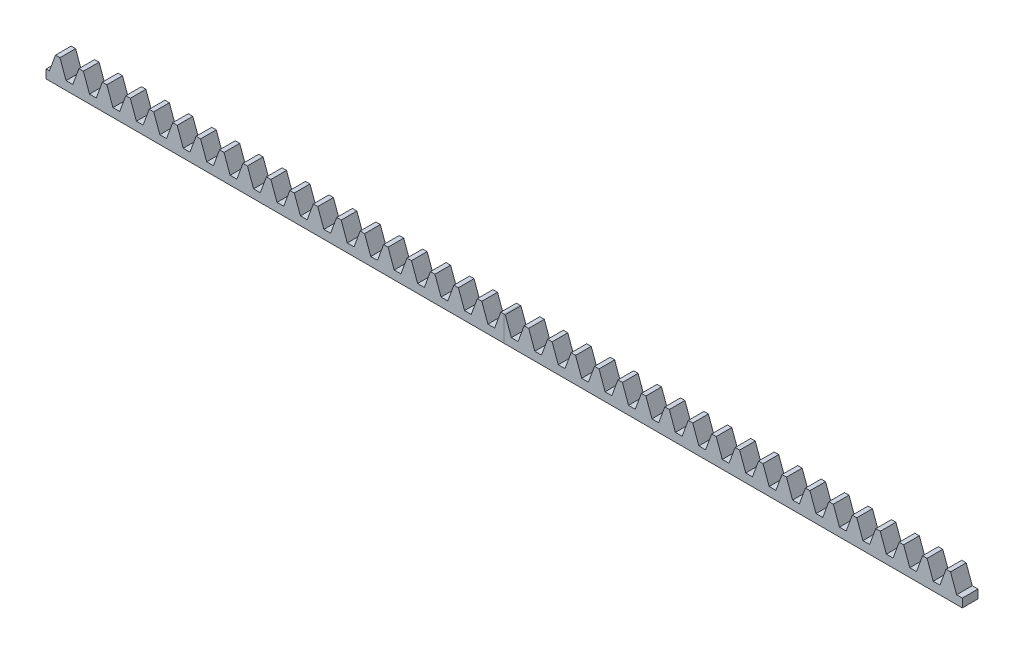
SolidWorks part; units mm, degrees
extrude "Blank" add sketch "BlankSke" against normal blind 8.89
sketch "BlankSke" plane through (0, 0, 0) normal (0, 0, 1) x (1, 0, 0)
  line L1 (0, 0) -> (519.999, 0)
  line L2 (0, 0) -> (0, 14.3933)
  line L3 (0, 14.3933) -> (519.999, 14.3933)
  line L4 (519.999, 0) -> (519.999, 14.3933)
  dimension "Length" = 519.999
  dimension "Blank_height" = 14.3933
ref_plane "Plane1" through (0, 0, 0) normal (0, 0, 1) x (1, 0, 0)
ref_plane "Plane2" through (0, 0, 0) normal (0, 1, 0) x (1, 0, 0)
ref_plane "Plane3" through (0, 0, 0) normal (1, 0, 0) x (0, 0, -1)
sketch "HoldingSke" plane through (0, 0, 0) normal (0, 1, 0) x (1, 0, 0)
  line L0 (0, 0) -> (116.7452, -97.9608)
  line L1 (-15, 0) -> (100, 0) construction
  line L2 (0, 0) -> (-2.1039, 2.3779)
  line L3 (0, 0) -> (-11.863, 4.5341)
  line L4 (0, 0) -> (6.5177, 5.6657)
  line L5 (0, 0) -> (-23.7986, -8.8762)
  line L6 (0, 0) -> (-10.5278, -7.1032)
  line L9 (-71.009, 38.7566) -> (417.6302, 216.6067)
  line L10 (-76.2, 71.12) -> (-66.04, 71.12)
  line L11 (0, 0) -> (-8.89, 0)
  line L12 (-76.2, 101.6) -> (-76.0298, 101.6)
  line L13 (24.9733, 27.94) -> (52.9518, 28.4284)
  line L14 (24.9733, 27.94) -> (24.9746, 27.94)
  line L15 (24.9733, 27.94) -> (100.4006, 29.5858)
  circle A0 centre (0, 0) radius 19.05
  circle A1 centre (0, 0) radius 5.08
  circle A2 centre (0, 0) radius 12.7
  dimension "MPH" = 10.16
  dimension "Diameter" = 38.1
  dimension "Num_teeth" = 41
  dimension "Pitch" = 152.4
  dimension "Show_teeth" = 400
  dimension "Thickness" = 12.7
  dimension "Ap" = 20
  dimension "Pitch_height" = 10.16
  dimension "Width" = 8.89
  dimension "Backlash" = 0.1702
  dimension "Addendum_fac" = 1
  dimension "Dedendum_fac" = 1.25
  dimension "Clearance_fac" = 0.25
  dimension "Dedendum_add" = 0.0013
  dimension "Length" = 519.999
sketch "TooCutSkeIll" plane through (0, 0, 0) normal (0, 0, 1) x (1, 0, 0)
  line L0 (-5.3356, 14.2819) -> (-2.1631, 5.5655)
  line L1 (-1.1674, 4.8683) -> (1.1674, 4.8683)
  line L2 (2.1631, 5.5655) -> (5.3356, 14.2819)
  line L3 (519.999, 14.3933) -> (0, 14.3933) construction
  line L4 (0, 0) -> (0, 64.897) construction
  line L5 (-13.208, 10.16) -> (12.954, 10.16) construction
  line L6 (0, 0) -> (519.999, 0) construction
  line L7 (3.8354, 10.16) -> (3.8354, 48.7463) construction
  line L8 (-3.8354, 10.16) -> (-3.8354, 48.7463) construction
  line L9 (5.4948, 14.3933) -> (5.4948, 14.4187)
  line L10 (-5.4948, 14.3933) -> (-5.4948, 14.4187)
  line L11 (-5.4948, 14.4187) -> (5.4948, 14.4187)
  arc A0 (1.1674, 4.8683) -> (2.1631, 5.5655) centre (1.1674, 5.9279) ccw
  arc A1 (-2.1631, 5.5655) -> (-1.1674, 4.8683) centre (-1.1674, 5.9279) ccw
  arc A2 (5.4948, 14.3933) -> (5.3356, 14.2819) centre (5.4948, 14.224) ccw
  arc A3 (-5.3356, 14.2819) -> (-5.4948, 14.3933) centre (-5.4948, 14.224) ccw
  dimension "Pitch_height" = 10.16
  dimension "Addendum_plus" = 4.2587
  dimension "Pressure_angle" = 20
  dimension "Gap_width" = 7.6708
  dimension "Dedendum" = 5.2917
extrude "ToothCutIll" [suppressed] cut sketch "TooCutSkeIll" against normal through all
sketch "TooCutSkeSim" plane through (0, 0, 0) normal (0, 0, 1) x (1, 0, 0)
  line L0 (1.9094, 4.8683) -> (-1.9094, 4.8683)
  line L1 (5.3854, 14.4187) -> (1.9094, 4.8683)
  line L2 (0, 17.4625) -> (0, 53.467) construction
  line L3 (5.3854, 14.4187) -> (-5.3854, 14.4187)
  line L6 (-5.3854, 14.4187) -> (-1.9094, 4.8683)
  line L9 (-3.8354, 10.16) -> (3.8354, 10.16) construction
  line L10 (0, 0) -> (519.999, 0) construction
  line L11 (3.8354, 10.16) -> (3.8354, 53.467) construction
  line L12 (-3.8354, 10.16) -> (-3.8354, 53.467) construction
  dimension "Pitch_height" = 10.16
  dimension "Addendum_plus" = 4.2587
  dimension "Pressure_angle" = 20
  dimension "Gap_width" = 7.6708
  dimension "Dedendum" = 5.2917
extrude "ToothCutSim" cut sketch "TooCutSkeSim" against normal through all
pattern_linear "TeethCuts" count 40 spacing 13.2994 along (1, 0, 0) of "ToothCutIll", "ToothCutSim"
ref_plane "Plane4" through (260, 0, 0) normal (-1, 0, 0) x (0, 0, 1)
split "Split1" trim tools "Plane4" bodies to split 102 resulting bodies 103 104
equation "' \"Pitch@HoldingSke\" = 4"
equation "' \"Num_teeth@HoldingSke\" = 12"
equation "' \"Ap@HoldingSke\" =  20"
equation "' \"Ap@HoldingSke\" = 20"
equation "' \"Width@HoldingSke\" = 0.25"
equation "' \"Show_teeth@HoldingSke\" = 500"
equation "' \"Backlash@HoldingSke\" = 0.009"
equation "' \"Addendum_fac@HoldingSke\" = 1.0"
equation "' \"Dedendum_fac@HoldingSke\" = 1.25"
equation "' \"Dedendum_add@HoldingSke\" = 0.00005"
equation "' \"Clearance_fac@HoldingSke\" = 0.25"
equation "' \"Pitch_height@HoldingSke\" = 1"
equation "' \"Length@HoldingSke\" = 4.71"
equation "\"MPH@HoldingSke\" = \"Dedendum_fac@HoldingSke\" / \"Pitch@HoldingSke\" + 2 * \"Dedendum_add@HoldingSke\" + 0.002"
equation "\"MPH@HoldingSke\" = ((sgn( \"MPH@HoldingSke\" - \"Pitch_height@HoldingSke\")+1)*( \"MPH@HoldingSke\" - \"Pitch_height@HoldingSke\"))/2 + \"Pitch_height@HoldingSke\""
equation "\"Blank_height@BlankSke\" = \"Pitch_height@HoldingSke\" + \"Addendum_fac@HoldingSke\"  / \"Pitch@HoldingSke\" "
equation "\"Length@BlankSke\" =  \"Length@HoldingSke\""
equation "\"Face_width@Blank\" = \"Width@HoldingSke\""
equation "\"Pressure_angle@TooCutSkeIll\" = \"Ap@HoldingSke\""
equation "\"Addendum_plus@TooCutSkeIll\" =  \"Addendum_fac@HoldingSke\"  / \"Pitch@HoldingSke\" + 0.001"
equation "\"Dedendum@TooCutSkeIll\" = \"Dedendum_fac@HoldingSke\"  / \"Pitch@HoldingSke\""
equation "\"Pitch_height@TooCutSkeIll\" =  \"MPH@HoldingSke\""
equation "\"Gap_width@TooCutSkeIll\" = 3.14159265 / 2 / \"Pitch@HoldingSke\" + 6 * \"Backlash@HoldingSke\""
equation "\"Pressure_angle@TooCutSkeSim\" = \"Ap@HoldingSke\""
equation "\"Addendum_plus@TooCutSkeSim\" =  \"Addendum_fac@HoldingSke\"  / \"Pitch@HoldingSke\" + 0.001"
equation "\"Dedendum@TooCutSkeSim\" = \"Dedendum_fac@HoldingSke\"  / \"Pitch@HoldingSke\""
equation "\"Pitch_height@TooCutSkeSim\" =  \"MPH@HoldingSke\""
equation "\"Gap_width@TooCutSkeSim\" = 3.14159265 / 2 / \"Pitch@HoldingSke\" + 6 * \"Backlash@HoldingSke\""
equation "\"Root_fillet@TooCutSkeIll\" = \"Clearance_fac@HoldingSke\" / \"Pitch@HoldingSke\" + \"Dedendum_add@HoldingSke\""
equation "\"Break_rad@TooCutSkeIll\" = 0.02 / \"Pitch@HoldingSke\" * 2"
equation "\"Linear_pitch@TeethCuts\" = 3.14159265 / \"Pitch@HoldingSke\""
equation "\"Num_teeth@HoldingSke\" = int( ( \"Length@HoldingSke\" + 0 ) / (3.14159265 / \"Pitch@HoldingSke\")) + 0.9999  + 1"
equation " \"Num_teeth@TeethCuts\" = int( \"Show_teeth@HoldingSke\" ) + 1"
equation " \"Num_teeth@TeethCuts\" = ((sgn( \"Num_teeth@TeethCuts\" - \"Num_teeth@HoldingSke\" )-1)*( \"Num_teeth@TeethCuts\" - \"Num_teeth@HoldingSke\" ))/-2+ \"Num_teeth@HoldingSke\""
equation " \"Num_teeth@TeethCuts\" = ((sgn( \"Num_teeth@TeethCuts\" - 2.0)+1)*( \"Num_teeth@TeethCuts\" - 2.0))/2 +2.0"
